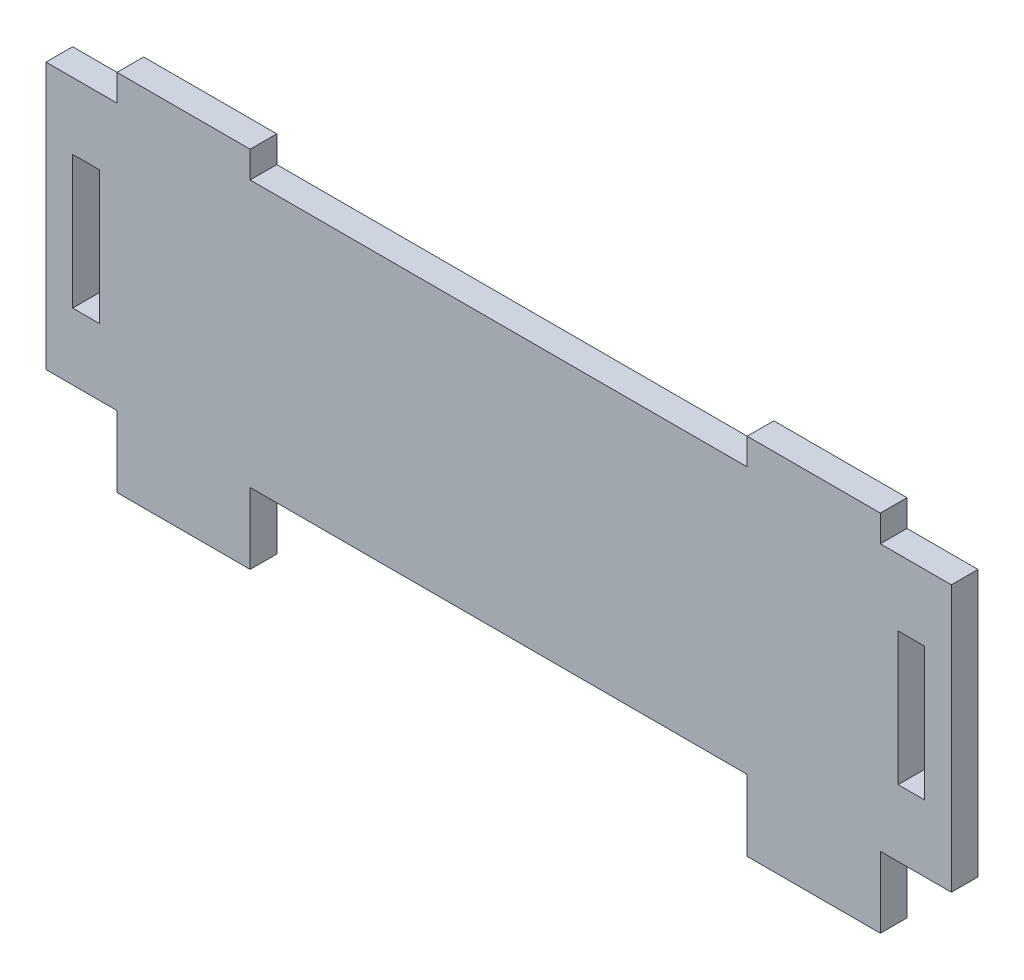
SolidWorks part; units mm, degrees
ref_plane "Front Plane" through (0, 0, 0) normal (0, 0, 1) x (1, 0, 0)
ref_plane "Top Plane" through (0, 0, 0) normal (0, 1, 0) x (1, 0, 0)
ref_plane "Right Plane" through (0, 0, 0) normal (1, 0, 0) x (0, 0, -1)
sketch "Sketch1" plane through (0, 0, 0) normal (0, 0, 1) x (1, 0, 0)
  line L0 (-51, 15) -> (-43, 15)
  line L6 (51, -15) -> (51, 15)
  line L8 (-51, -15) -> (-51, 15)
  line L9 (-43, 15) -> (-43, 18)
  line L10 (-43, 18) -> (-28, 18)
  line L15 (-28, 18) -> (-28, 15)
  line L16 (-28, 15) -> (28, 15)
  line L19 (28, 18) -> (43, 18)
  line L21 (28, 15) -> (28, 18)
  line L22 (43, 18) -> (43, 15)
  line L23 (-43, -23) -> (-28, -23)
  line L27 (43, 15) -> (51, 15)
  line L28 (51, -15) -> (43, -15)
  line L29 (43, -23) -> (28, -23)
  line L30 (43, -15) -> (43, -23)
  line L32 (28, -23) -> (28, -15)
  line L33 (28, -15) -> (-28, -15)
  line L34 (-28, -15) -> (-28, -23)
  line L35 (-43, -23) -> (-43, -15)
  line L36 (-43, -15) -> (-51, -15)
  line L38 (-48, 7.5) -> (-45, 7.5)
  line L39 (-48, 7.5) -> (-48, -7.5)
  line L40 (-48, -7.5) -> (-45, -7.5)
  line L41 (-45, 7.5) -> (-45, -7.5)
  line L44 (45, 7.5) -> (48, 7.5)
  line L45 (45, 7.5) -> (45, -7.5)
  line L46 (45, -7.5) -> (48, -7.5)
  line L47 (48, 7.5) -> (48, -7.5)
  point P0 (0, 0)
  point P2 (-28, 15)
  point P13 (-43, 15)
  point P14 (-43, -15)
  point P15 (-51, 15)
  point P16 (-51, -15)
  point P17 (-28, -15)
  point P28 (-43, -23)
  point P29 (-28, 18)
  point P30 (-43, 18)
  point P31 (-28, -23)
  point P32 (28, -15)
  point P33 (43, -15)
  point P34 (28, -23)
  point P35 (43, -23)
  point P36 (43, 15)
  point P37 (51, -15)
  point P38 (51, 15)
  point P39 (28, 15)
  point P40 (43, 18)
  point P41 (28, 18)
extrude "Boss-Extrude1" add sketch "Sketch1" along normal blind 3 contours L8 L0 L9 L10 L15 L16 L21 L19 L22 L27 L6 L28 L30 L29 L32 L33 L34 L23 L35 L36 | L41 L40 L39 L38 | L47 L46 L45 L44
